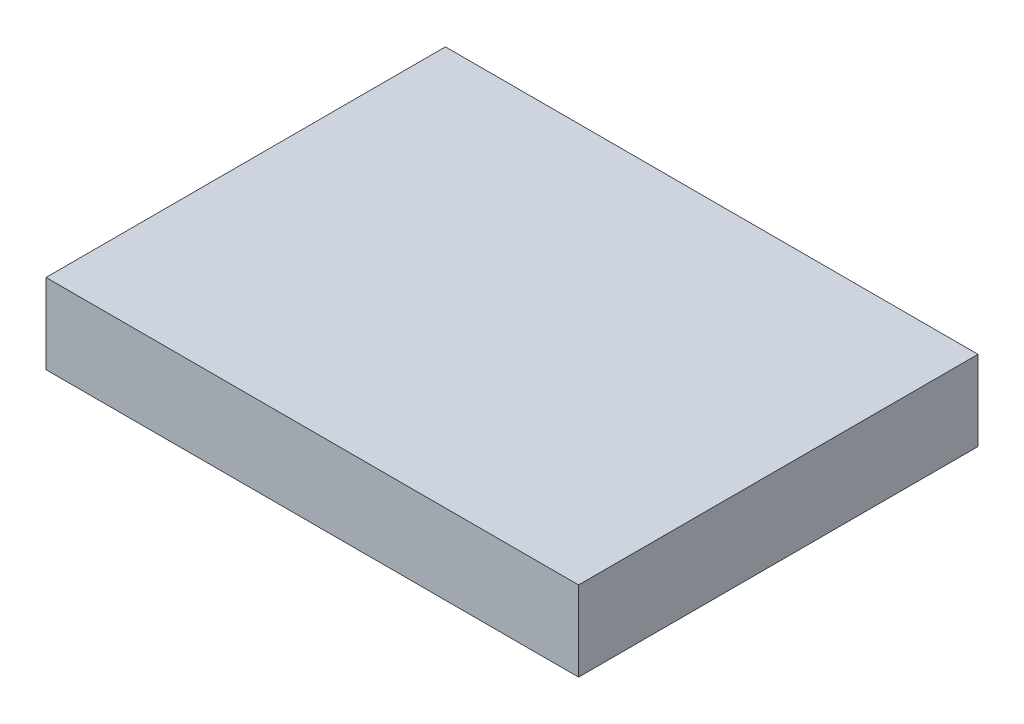
SolidWorks part; units mm, degrees
ref_plane "Спереди" through (0, 0, 0) normal (0, 0, 1) x (1, 0, 0)
ref_plane "Сверху" through (0, 0, 0) normal (0, 1, 0) x (1, 0, 0)
ref_plane "Справа" through (0, 0, 0) normal (1, 0, 0) x (0, 0, -1)
other "Configuration Table"
sketch "Эскиз1" plane through (0, 0, 0) normal (0, 1, 0) x (1, 0, 0)
  line L1 (10, -7.5) -> (-10, -7.5)
  line L2 (10, -7.5) -> (10, 7.5)
  line L3 (10, 7.5) -> (-10, 7.5)
  line L4 (-10, -7.5) -> (-10, 7.5)
  line L5 (10, -7.5) -> (-10, 7.5) construction
  line L6 (10, 7.5) -> (-10, -7.5) construction
  point P0 (0, 0)
extrude "Бобышка-Вытянуть1" add sketch "Эскиз1" along normal blind 3
